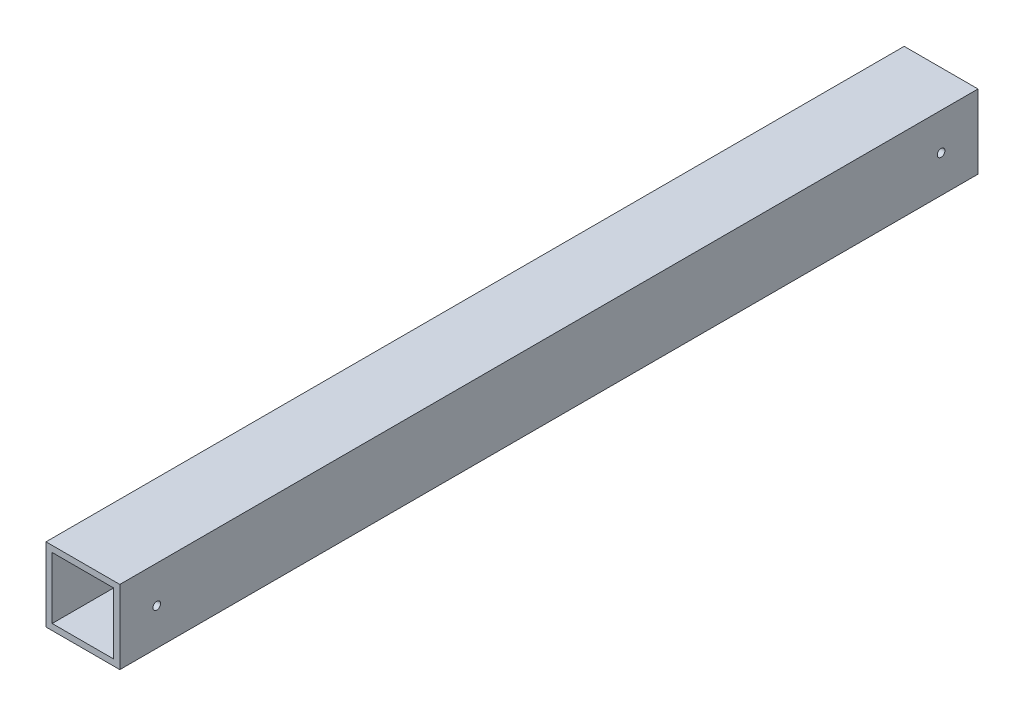
SolidWorks part; units mm, degrees
ref_plane "前视基准面" through (0, 0, 0) normal (0, 0, 1) x (1, 0, 0)
ref_plane "上视基准面" through (0, 0, 0) normal (0, 1, 0) x (1, 0, 0)
ref_plane "右视基准面" through (0, 0, 0) normal (1, 0, 0) x (0, 0, -1)
sketch "草图1" plane through (0, 0, 0) normal (0, 0, 1) x (1, 0, 0)
  line L0 (-12, 12) -> (12, 12)
  line L1 (-10, 10) -> (10, 10)
  line L2 (-10, 10) -> (-10, -10)
  line L3 (-10, -10) -> (10, -10)
  line L4 (10, 10) -> (10, -10)
  line L5 (-10, 10) -> (10, -10) construction
  line L6 (-10, -10) -> (10, 10) construction
  line L7 (12, 12) -> (12, -12)
  line L8 (-12, -12) -> (12, -12)
  line L9 (-12, 12) -> (-12, -12)
  point P0 (0, 0)
  dimension "D1" = 20
  dimension "D2" = 20
  dimension "D3" = 2
extrude "凸台-拉伸1" add sketch "草图1" along normal mid plane 279
sketch "草图5" plane through (-12, 0, 0) normal (-1, 0, 0) x (0, 0, 1)
  line L0 (-139.5, 12) -> (-139.5, -12) construction
  circle A0 centre (-127.5, 0) radius 2 construction
  dimension "D1" = 12
hole_wizard "M3 螺纹孔的螺纹孔钻头2" positions "3D草图2" profile "草图6" hole size "M3" standard "GB" end condition through all
sketch3d "3D草图2"
  point P0 (-12, 0, -127.5)
sketch "草图6" plane through (-12, 0, -127.5) normal (0, 1, 0) x (0, 0, 1)
  line L0 (0, 0) -> (0, 24)
  line L1 (0, 24) -> (1.25, 24)
  line L2 (1.25, 24) -> (1.25, 0)
  line L5 (1.25, 0) -> (0, 0)
  line L11 (0, -6.35) -> (0, 107.95) construction
  dimension "通孔孔直径" = 2.5
  dimension "通孔孔深度" = 24
mirror "镜向1" about plane through (0, 0, 0) normal (0, 0, 1) of "M3 螺纹孔的螺纹孔钻头2"
